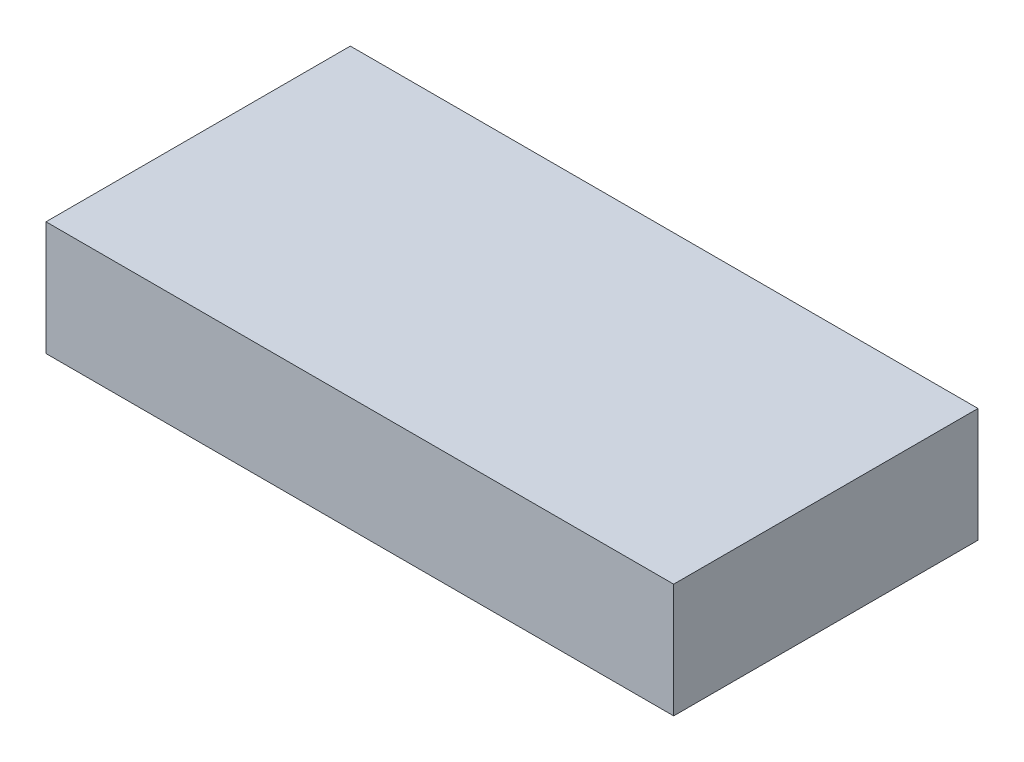
SolidWorks part; units mm, degrees
ref_plane "Front Plane" through (0, 0, 0) normal (0, 0, 1) x (1, 0, 0)
ref_plane "Top Plane" through (0, 0, 0) normal (0, 1, 0) x (1, 0, 0)
ref_plane "Right Plane" through (0, 0, 0) normal (1, 0, 0) x (0, 0, -1)
sketch "Sketch1" plane through (0, 0, 0) normal (0, 1, 0) x (1, 0, 0)
  line L1 (-16.5, -8) -> (16.5, -8)
  line L2 (-16.5, -8) -> (-16.5, 8)
  line L3 (-16.5, 8) -> (16.5, 8)
  line L4 (16.5, -8) -> (16.5, 8)
  line L5 (-16.5, -8) -> (16.5, 8) construction
  line L6 (-16.5, 8) -> (16.5, -8) construction
  point P0 (0, 0)
  dimension "D1" = 33
  dimension "D2" = 16
extrude "Boss-Extrude1" add sketch "Sketch1" along normal mid plane 6
